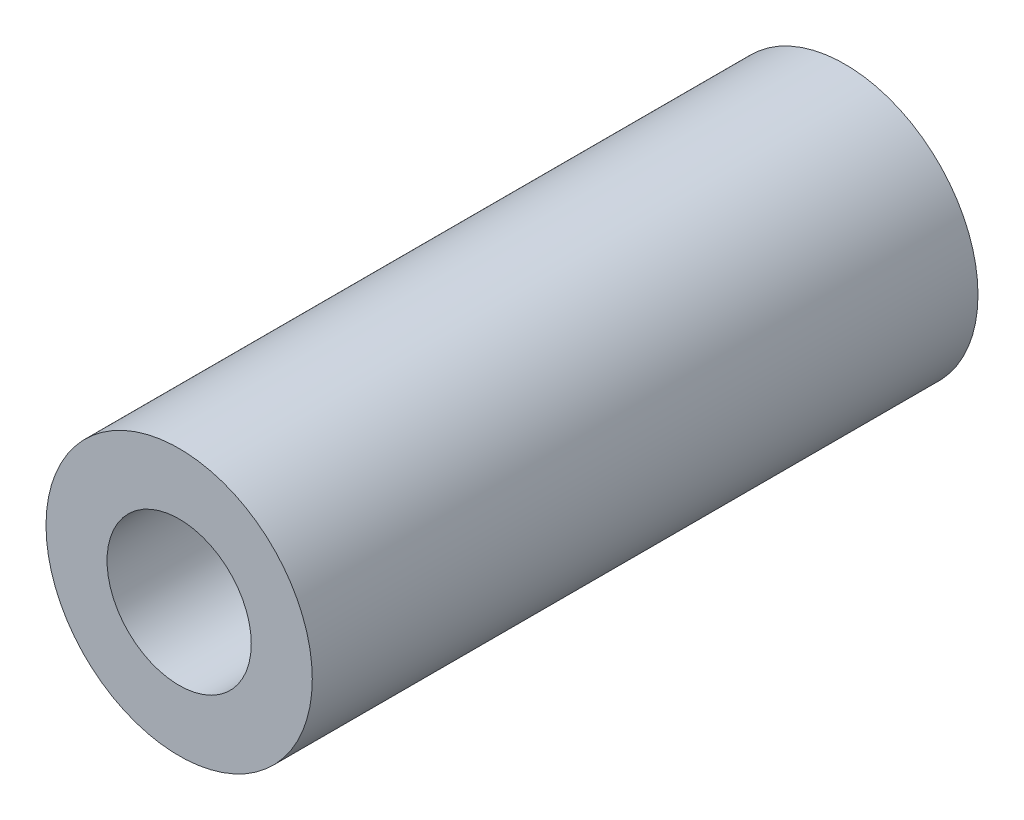
SolidWorks part; units mm, degrees
ref_plane "Front Plane" through (0, 0, 0) normal (1, 0, 0) x (0, 1, 0)
ref_plane "Top Plane" through (0, 0, 0) normal (0, 0, 1) x (0, 1, 0)
ref_plane "Right Plane" through (0, 0, 0) normal (0, 1, 0) x (-1, 0, 0)
sketch "Sketch1" plane through (0, 0, 0) normal (0, 0, 1) x (0, 1, 0)
  circle A0 centre (0, 0) radius 3.25
  circle A1 centre (0, 0) radius 6
  dimension "D1" = 12
  dimension "D2" = 6.5
extrude "Boss-Extrude1" add sketch "Sketch1" along normal blind 30
